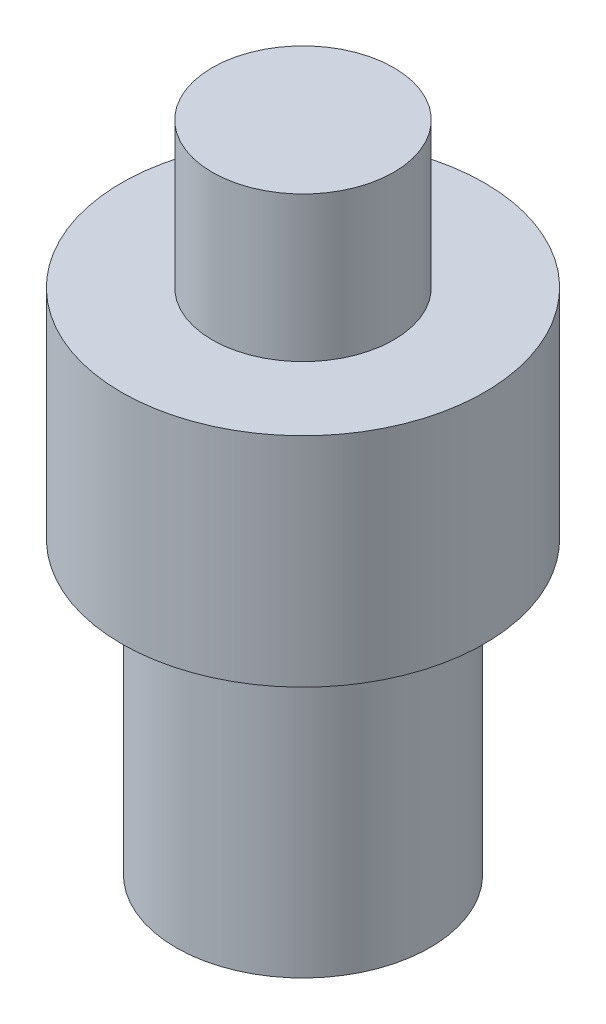
SolidWorks part; units mm, degrees
ref_plane "前视基准面" through (0, 0, 0) normal (0, 0, 1) x (1, 0, 0)
ref_plane "上视基准面" through (0, 0, 0) normal (0, 1, 0) x (1, 0, 0)
ref_plane "右视基准面" through (0, 0, 0) normal (1, 0, 0) x (0, 0, -1)
sketch "草图1" plane through (0, 0, 0) normal (0, 0, 1) x (1, 0, 0)
  line L0 (0, -45) -> (0, 45) construction
  line L1 (0, -45) -> (17.5, -45)
  line L2 (17.5, -45) -> (17.5, -5)
  line L3 (17.5, -5) -> (25, -5)
  line L4 (25, -5) -> (25, 25)
  line L5 (25, 25) -> (12.5, 25)
  line L6 (12.5, 25) -> (12.5, 45)
  line L7 (12.5, 45) -> (0, 45)
  line L8 (0, 45) -> (0, -45)
revolve "旋转1" add sketch "草图1" angle 360 about L0
